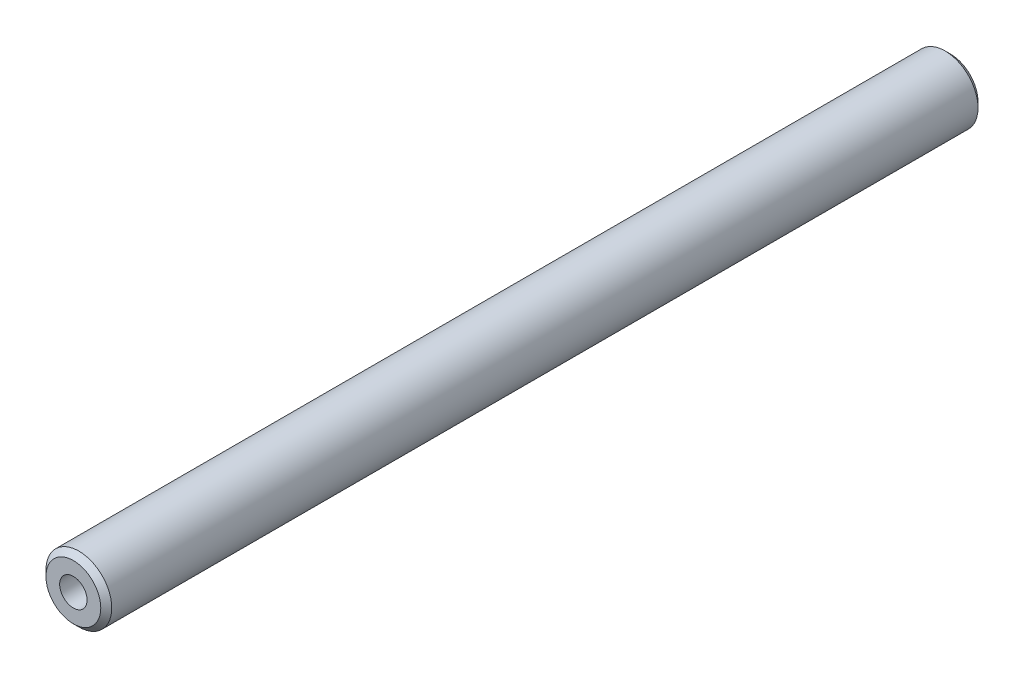
SolidWorks part; units mm, degrees
material "A2017"
ref_plane "正面" through (0, 0, 0) normal (0, 0, 1) x (1, 0, 0)
ref_plane "平面" through (0, 0, 0) normal (0, 1, 0) x (1, 0, 0)
ref_plane "右側面" through (0, 0, 0) normal (1, 0, 0) x (0, 0, -1)
sketch "ｽｹｯﾁ1" plane through (0, 0, 0) normal (0, 0, 1) x (1, 0, 0)
  circle A0 centre (0, 0) radius 3
  dimension "D1" = 6
extrude "ﾎﾞｽ - 押し出し1" add sketch "ｽｹｯﾁ1" along normal mid plane 80
chamfer "面取り1" distance 0.5 angle 45 2 edges at (3, 0, -40) (3, 0, 40)
hole_wizard "M3 ねじ穴1" positions "ｽｹｯﾁ2" profile "ｽｹｯﾁ3" tap size "M3" standard "JIS"
sketch "ｽｹｯﾁ2" plane through (0, 0, 40) normal (0, 0, 1) x (1, 0, 0)
  point P0 (0, 0)
sketch "ｽｹｯﾁ3" plane through (0, 0, 40) normal (1, 0, 0) x (0, -1, 0)
  line L0 (0, 0) -> (0, 9.2511)
  line L1 (0, 9.2511) -> (1.25, 8.5)
  line L2 (1.25, 8.5) -> (1.25, 0)
  line L5 (1.25, 0) -> (0, 0)
  line L10 (0, 9.2511) -> (-1.25, 8.5) construction
  line L11 (0, -6.35) -> (0, 107.95) construction
  dimension "ねじ下穴ﾄﾞﾘﾙ直径" = 2.5
  dimension "ねじ下穴ﾄﾞﾘﾙの深さ" = 8.5
  dimension "ﾄﾞﾘﾙ角度" = 118
cosmetic thread "穴のねじ山1" parameters "D1"=6, "D2"=3
mirror "ﾐﾗｰ1" about plane through (0, 0, 0) normal (0, 0, 1) of "M3 ねじ穴1"
